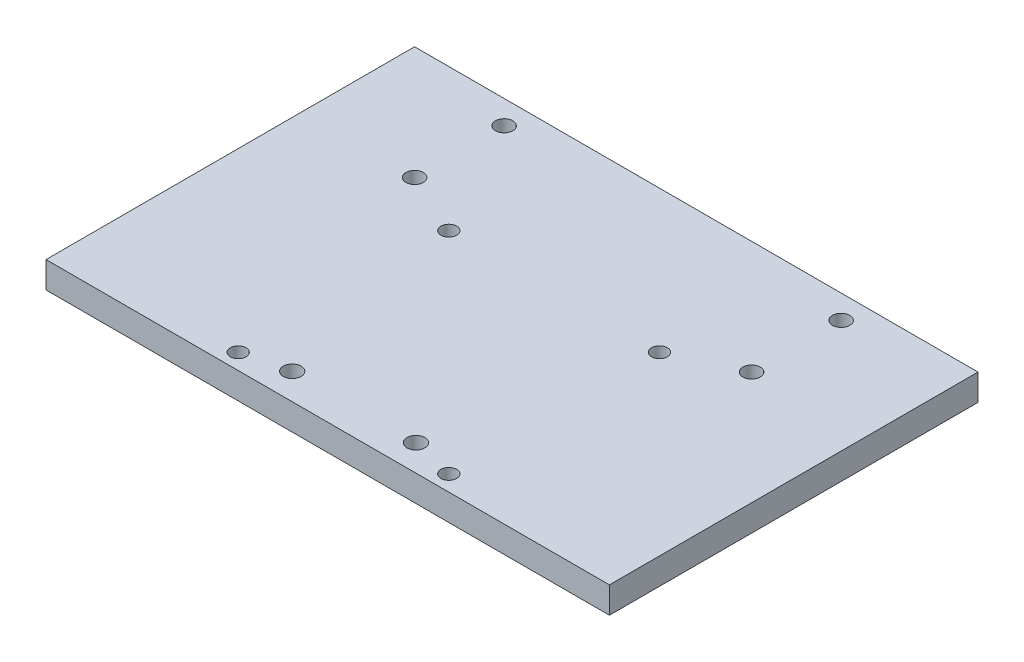
SolidWorks part; units mm, degrees
ref_plane "前视基准面" through (0, 0, 0) normal (0, 0, 1) x (1, 0, 0)
ref_plane "上视基准面" through (0, 0, 0) normal (0, 1, 0) x (1, 0, 0)
ref_plane "右视基准面" through (0, 0, 0) normal (1, 0, 0) x (0, 0, -1)
sketch "草图1" plane through (0, 0, 0) normal (0, 1, 0) x (1, 0, 0)
  line L1 (-50.6924, 20.5109) -> (56.3076, 20.5109)
  line L2 (-50.6924, 20.5109) -> (-50.6924, -49.4891)
  line L3 (-50.6924, -49.4891) -> (56.3076, -49.4891)
  line L4 (56.3076, 20.5109) -> (56.3076, -49.4891)
  dimension "D1" = 107
  dimension "D2" = 70
extrude "凸台-拉伸1" add sketch "草图1" along normal blind 5
sketch "草图2" plane through (0, 0, 0) normal (0, -1, 0) x (1, 0, 0)
  line L0 (2.8076, 49.4891) -> (2.8076, -20.5109) construction
  line L1 (-50.6924, 49.4891) -> (56.3076, 49.4891) construction
  line L2 (56.3076, -20.5109) -> (-50.6924, -20.5109) construction
  line L3 (-50.6924, -7.5109) -> (55.5808, -7.5109) construction
  line L4 (-50.6924, -20.5109) -> (-50.6924, 49.4891) construction
  line L5 (-50.6924, 26.4891) -> (56.3076, 26.4891) construction
  line L6 (56.3076, 49.4891) -> (56.3076, -20.5109) construction
  circle A0 centre (-8.9424, 44.4891) radius 1.7
  circle A1 centre (-29.1924, -16.0109) radius 1.65
  circle A2 centre (-29.1924, 0.9891) radius 1.65
  circle A3 centre (14.5576, 44.4891) radius 1.7
  circle A4 centre (34.8076, -16.0109) radius 1.65
  circle A5 centre (34.8076, 0.9891) radius 1.65
  circle A6 centre (-17.1924, 46.4891) radius 1.5
  circle A7 centre (-17.1924, 6.4891) radius 1.5
  circle A8 centre (22.8076, 46.4891) radius 1.5
  circle A9 centre (22.8076, 6.4891) radius 1.5
  dimension "D1" = 3.4
  dimension "D4" = 3.3
  dimension "D8" = 3
  dimension "D2" = 11.75
  dimension "D3" = 5
  dimension "D5" = 8.5
  dimension "D6" = 32
  dimension "D7" = 13
  dimension "D9" = 20
  dimension "D10" = 20
  dimension "D11" = 23
extrude "切除-拉伸1" cut sketch "草图2" against normal blind 5 contours A1 | A0 | A4 | A5 | A2 | A7 | A8 | A3 | A6 | A9
